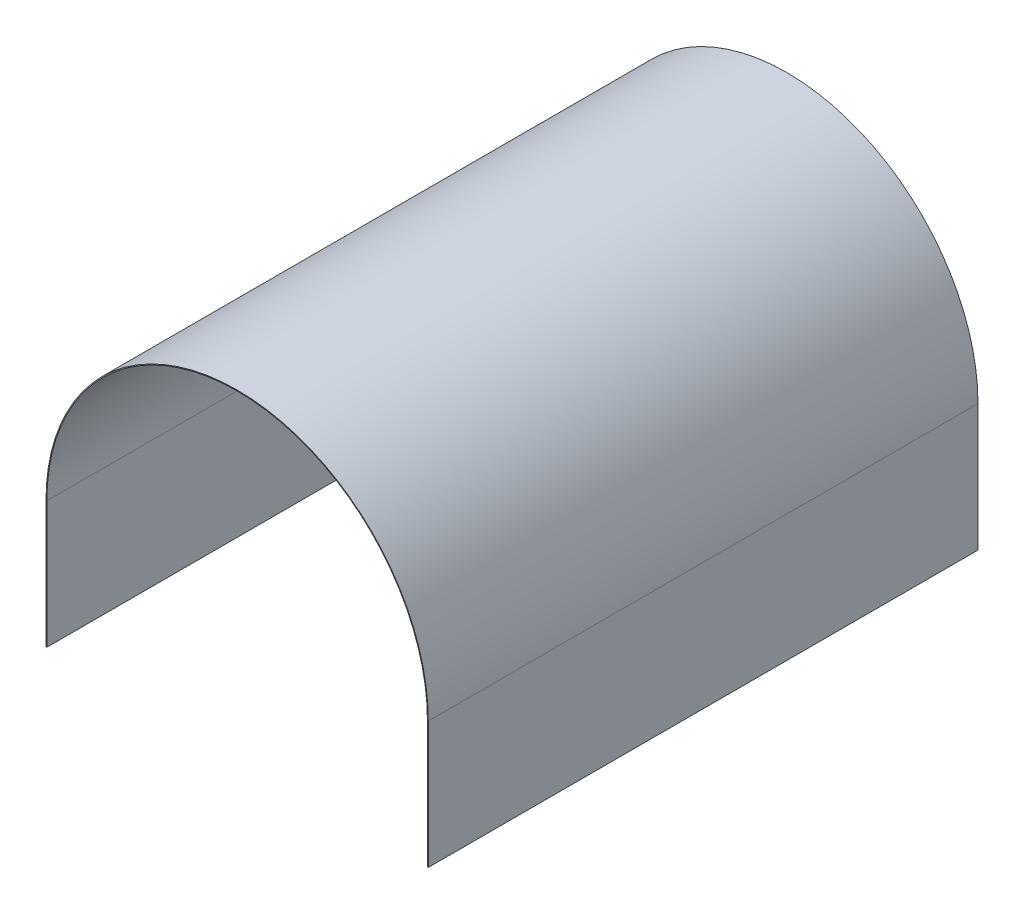
SolidWorks part; units mm, degrees
ref_plane "Front Plane" through (0, 0, 0) normal (0, 0, 1) x (1, 0, 0)
ref_plane "Top Plane" through (0, 0, 0) normal (0, 1, 0) x (1, 0, 0)
ref_plane "Right Plane" through (0, 0, 0) normal (1, 0, 0) x (0, 0, -1)
sketch "Sketch1" plane through (0, 0, 0) normal (0, 0, 1) x (1, 0, 0)
  line L0 (-228.6, -36.83) -> (-228.6, -189.23)
  line L1 (-228.6, -189.23) -> (230.632, -189.23)
  line L2 (-228.6, -189.23) -> (-228.6, 192.786) construction
  line L3 (-228.6, 192.786) -> (230.632, 192.786) construction
  line L4 (230.632, -189.23) -> (230.632, 192.786) construction
  line L5 (230.632, -36.83) -> (230.632, -189.23)
  circle A0 centre (0, 0) radius 127 construction
  arc A2 (230.632, -36.83) -> (-228.6, -36.83) centre (1.016, -36.83) ccw
  dimension "D1" = 254
  dimension "D4" = 189.23
  dimension "D5" = 228.6
  dimension "D2" = 459.232
  dimension "D3" = 382.016
extrude "Boss-Extrude1" add sketch "Sketch1" along normal blind 660.4
sketch "Sketch2" plane through (0, 0, 660.4) normal (0, 0, 1) x (1, 0, 0)
  line L0 (-228.6, -189.23) -> (230.632, -189.23) construction
  line L2 (-227.584, -36.83) -> (-227.584, -189.23)
  line L3 (-227.584, -189.23) -> (229.616, -189.23)
  line L4 (229.616, -36.83) -> (229.616, -189.23)
  line L5 (-187.6415, 88.9417) -> (229.616, -189.23) construction
  line L6 (-227.584, -189.23) -> (189.6735, 88.9417) construction
  arc A1 (229.616, -36.83) -> (-227.584, -36.83) centre (1.016, -36.83) ccw
  dimension "D2" = 457.2
extrude "Cut-Extrude1" cut sketch "Sketch2" against normal blind 660.4
